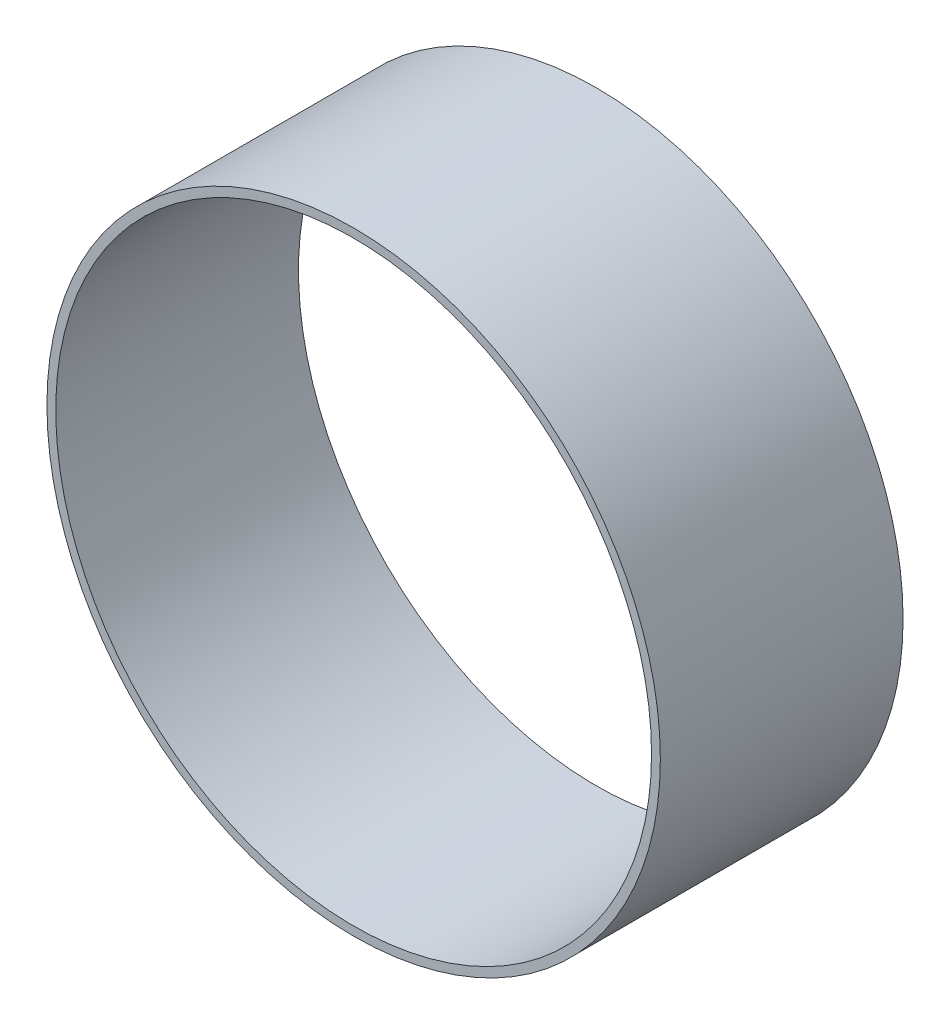
SolidWorks part; units mm, degrees
ref_plane "Спереди" through (0, 0, 0) normal (0, 0, 1) x (1, 0, 0)
ref_plane "Сверху" through (0, 0, 0) normal (0, 1, 0) x (1, 0, 0)
ref_plane "Справа" through (0, 0, 0) normal (1, 0, 0) x (0, 0, -1)
sketch "Эскиз1" plane through (0, 0, 0) normal (0, 0, 1) x (1, 0, 0)
  circle A0 centre (0, 0) radius 69.5
  circle A1 centre (0, 0) radius 67.5
extrude "Printed_fixed_case" add sketch "Эскиз1" along normal blind 55 from offset 27
